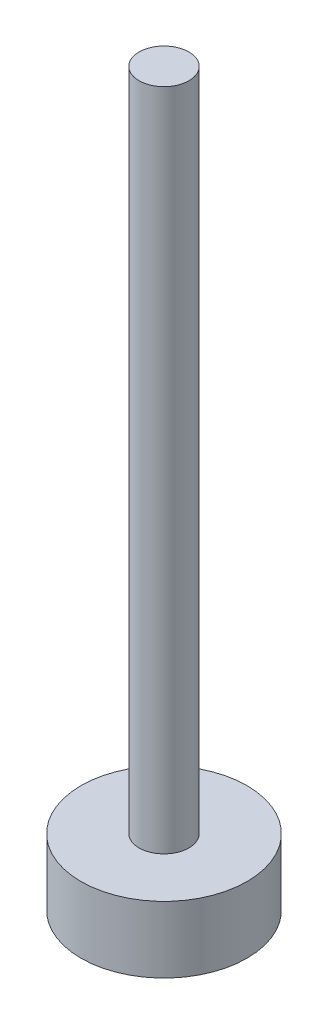
SolidWorks part; units mm, degrees
ref_plane "Front View" through (0, 0, 0) normal (0, 0, 1) x (1, 0, 0)
ref_plane "Upper View" through (0, 0, 0) normal (0, 1, 0) x (1, 0, 0)
ref_plane "Right View" through (0, 0, 0) normal (1, 0, 0) x (0, 0, -1)
sketch "Sketch2" plane through (0, 0, 0) normal (0, 1, 0) x (1, 0, 0)
  circle A0 centre (0, 0) radius 25
extrude "Boss-Extrude3" add sketch "Sketch2" along normal blind 20
sketch "Sketch3" plane through (0, 20, 0) normal (0, 1, 0) x (1, 0, 0)
  circle A0 centre (0, 0) radius 7.5
extrude "Boss-Extrude4" add sketch "Sketch3" along normal blind 200
